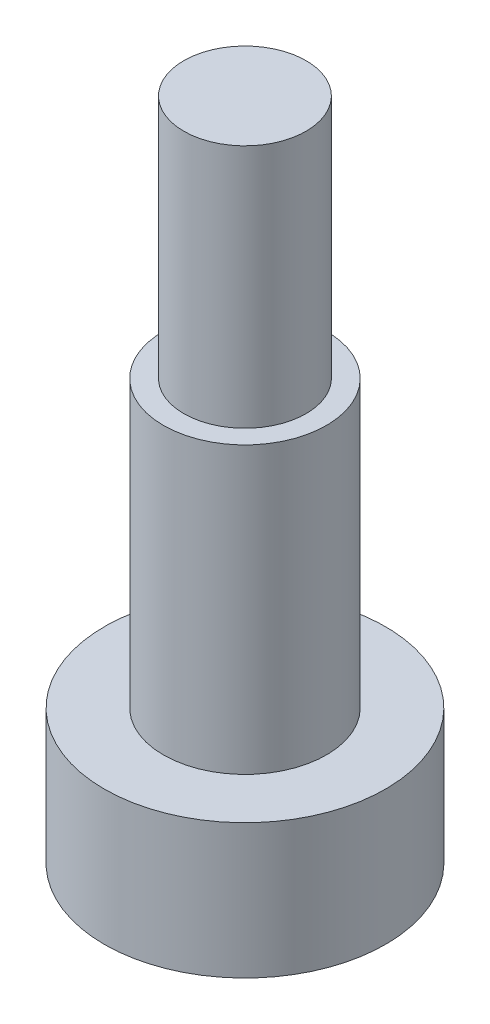
SolidWorks part; units mm, degrees
material "6061 合金"
ref_plane "Front Plane" through (0, 0, 0) normal (0, 0, 1) x (1, 0, 0)
ref_plane "Top Plane" through (0, 0, 0) normal (0, 1, 0) x (1, 0, 0)
ref_plane "Right Plane" through (0, 0, 0) normal (1, 0, 0) x (0, 0, -1)
other "Configuration Table"
sketch "草图1" plane through (0, 0, 0) normal (0, 1, 0) x (1, 0, 0)
  circle A0 centre (0, 0) radius 3.45
  dimension "D1" = 6.9
extrude "凸台-拉伸1" add sketch "草图1" along normal blind 3.3
sketch "草图2" plane through (0, 3.3, 0) normal (0, 1, 0) x (1, 0, 0)
  circle A0 centre (0, 0) radius 2
  dimension "D1" = 4
extrude "凸台-拉伸2" add sketch "草图2" along normal blind 7
sketch "草图3" plane through (0, 10.3, 0) normal (0, 1, 0) x (1, 0, 0)
  circle A0 centre (0, 0) radius 1.5
  dimension "D1" = 3
extrude "凸台-拉伸3" add sketch "草图3" along normal blind 6
